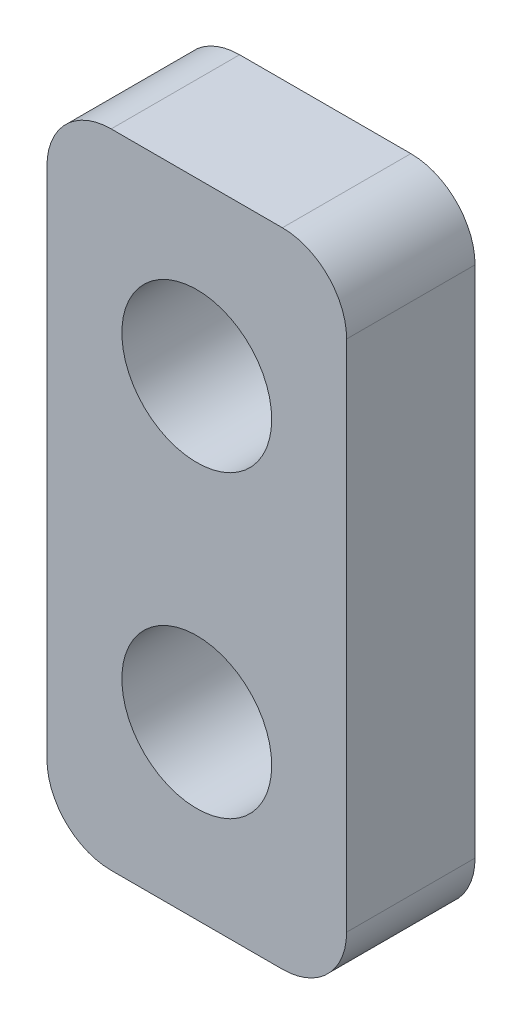
SolidWorks part; units mm, degrees
ref_plane "Front Plane" through (0, 0, 0) normal (0, 0, 1) x (1, 0, 0)
ref_plane "Top Plane" through (0, 0, 0) normal (0, 1, 0) x (1, 0, 0)
ref_plane "Right Plane" through (0, 0, 0) normal (1, 0, 0) x (0, 0, -1)
sketch "Sketch1" plane through (0, 0, 0) normal (0, 0, 1) x (1, 0, 0)
  line L1 (3, 0) -> (11, 0)
  line L2 (0, 3) -> (0, 27)
  line L3 (3, 30) -> (11, 30)
  line L4 (14, 3) -> (14, 27)
  arc A0 (3, 0) -> (0, 3) centre (3, 3) cw
  arc A1 (11, 0) -> (14, 3) centre (11, 3) ccw
  arc A2 (11, 30) -> (14, 27) centre (11, 27) cw
  arc A3 (0, 27) -> (3, 30) centre (3, 27) cw
  circle A4 centre (7, 22) radius 3.5
  circle A5 centre (7, 8) radius 3.5
  point P7 (0, 0)
  point P12 (14, 30)
  point P15 (0, 30)
  dimension "D3" = 3
  dimension "D4" = 7
  dimension "D5" = 7
  dimension "D1" = 14
  dimension "D2" = 30
  dimension "D6" = 8
  dimension "D7" = 14
  dimension "D8" = 8
  dimension "D9" = 7
extrude "Boss-Extrude1" add sketch "Sketch1" along normal blind 6
